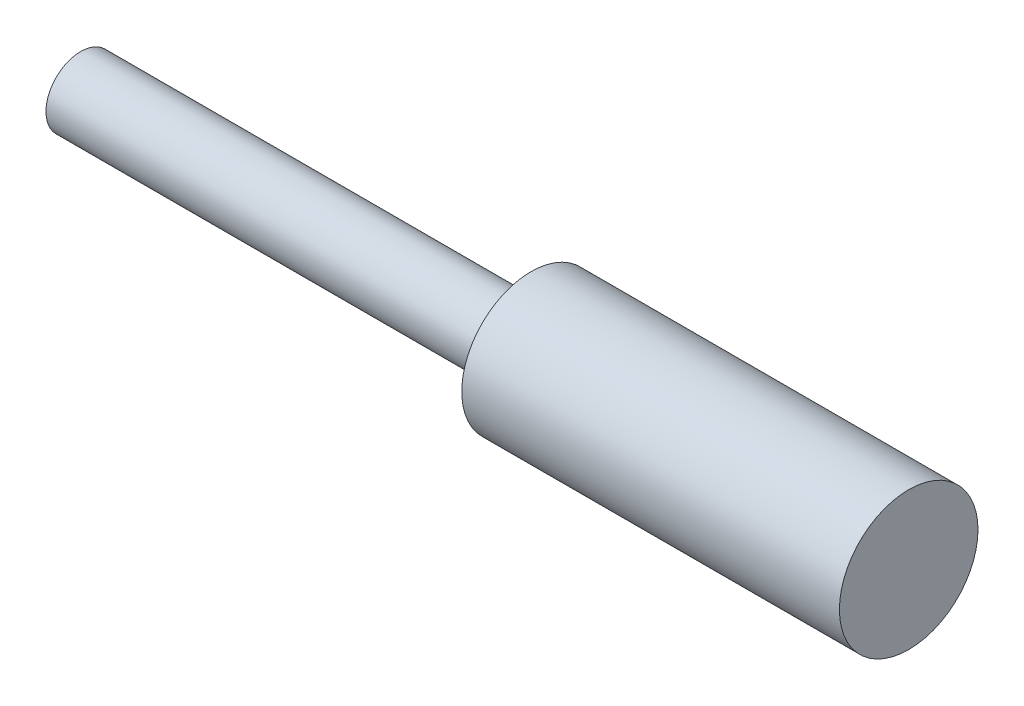
SolidWorks part; units mm, degrees
ref_plane "Front" through (0, 0, 0) normal (0, 0, 1) x (1, 0, 0)
ref_plane "Top" through (0, 0, 0) normal (0, 1, 0) x (1, 0, 0)
ref_plane "Right" through (0, 0, 0) normal (1, 0, 0) x (0, 0, -1)
sketch "Sketch3" plane through (2657.7384, 0, 0) normal (-1, 0, 0) x (0, 0, 1)
  circle A0 centre (22.5744, 11.5) radius 3 construction
  circle A1 centre (22.5744, 11.5) radius 3
extrude "Base-Extrude" add sketch "Sketch3" against normal up to surface (71.7 mm away)
sketch "Sketch4" plane through (2729.4384, 0, 0) normal (-1, 0, 0) x (0, 0, 1)
  circle A1 centre (22.5744, 11.5) radius 6 construction
  circle A2 centre (22.5744, 11.5) radius 6
extrude "Boss-Extrude1" add sketch "Sketch4" along normal up to surface (32.7 mm away)
